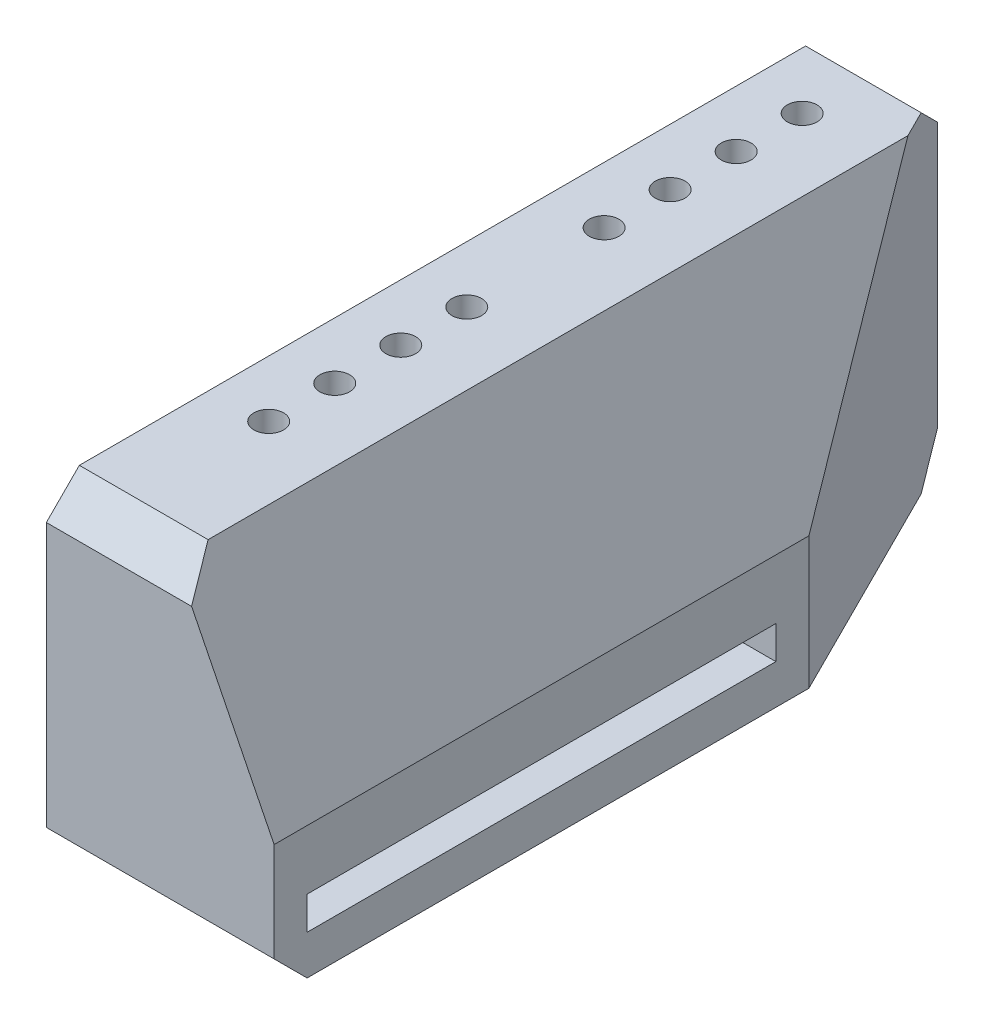
SolidWorks part; units mm, degrees
ref_plane "Front Plane" through (0, 0, 0) normal (0, 0, 1) x (1, 0, 0)
ref_plane "Top Plane" through (0, 0, 0) normal (0, 1, 0) x (1, 0, 0)
ref_plane "Right Plane" through (0, 0, 0) normal (1, 0, 0) x (0, 0, -1)
sketch "Sketch1" plane through (0, 0, 0) normal (1, 0, 0) x (0, 0, -1)
  line L1 (-60, -25) -> (60, -25)
  line L2 (-60, -25) -> (-60, 25)
  line L3 (-60, 25) -> (60, 25)
  line L4 (60, -25) -> (60, 25)
  line L5 (-60, -25) -> (60, 25) construction
  line L6 (-60, 25) -> (60, -25) construction
  point P0 (0, 0)
  dimension "D1" = 50
  dimension "D2" = 120
extrude "Boss-Extrude1" add sketch "Sketch1" along normal blind 34.5
sketch "Sketch2" plane through (34.5, 0, 0) normal (1, 0, 0) x (0, 0, -1)
  line L0 (-60, 25) -> (-60, -25) construction
  line L1 (-55, -19) -> (16, -19)
  line L2 (-55, -19) -> (-55, -14)
  line L3 (-55, -14) -> (16, -14)
  line L4 (16, -19) -> (16, -14)
  line L5 (-55, -19) -> (16, -14) construction
  line L6 (-55, -14) -> (16, -19) construction
  line L7 (-60, -25) -> (60, -25) construction
  point P0 (-19.5, -16.5)
  dimension "D1" = 71
  dimension "D2" = 5
  dimension "D3" = 5
  dimension "D4" = 6
extrude "Cut-Extrude1" cut sketch "Sketch2" against normal blind 16
hole_wizard "M4 Clearance Hole1" positions "Sketch3" profile "Sketch5" hole size "M4" standard "ANSI Metric"
sketch "Sketch3" plane through (0, -25, 0) normal (0, -1, 0) x (-1, 0, 0)
  line L0 (-24.5, -50) -> (-24.5, 10)
  line L2 (-34.5, -60) -> (-34.5, 60) construction
  line L3 (-34.5, -60) -> (0, -60) construction
  point P1 (-24.5, -50)
  point P2 (-24.5, 10)
  dimension "D1" = 10
  dimension "D2" = 10
  dimension "D3" = 60
sketch "Sketch5" plane through (24.5, -25, 50) normal (1, 0, 0) x (0, 0, -1)
  line L0 (0, 0) -> (0, 6)
  line L1 (0, 6) -> (2.25, 6)
  line L2 (2.25, 6) -> (2.25, 0)
  line L5 (2.25, 0) -> (0, 0)
  line L11 (0, -6.35) -> (0, 107.95) construction
  dimension "Thru Hole Dia." = 4.5
  dimension "Thru Hole Depth" = 6
hole_wizard "M4 Clearance Hole2" positions "Sketch6" profile "Sketch8" hole size "M4" standard "ANSI Metric"
sketch "Sketch6" plane through (0, 25, 0) normal (0, 1, 0) x (1, 0, 0)
  line L0 (8.58, 15.9) -> (8.58, -34.9)
  line L1 (0, 60) -> (0, -60) construction
  line L3 (34.5, -55) -> (34.5, 16) construction
  line L4 (34.5, -55) -> (34.5, 16)
  point P1 (8.58, 15.9)
  point P2 (8.58, -34.9)
  point P20 (8.58, -9.5)
  point P21 (34.5, -19.5)
  point P22 (8.58, 10.6774)
  dimension "D1" = 50.8
  dimension "D2" = 8.58
  dimension "D3" = 10
sketch "Sketch8" plane through (8.58, 25, -15.9) normal (1, 0, 0) x (0, 0, 1)
  line L0 (0, 0) -> (0, 7.3519)
  line L1 (0, 7.3519) -> (2.25, 6)
  line L2 (2.25, 6) -> (2.25, 0)
  line L5 (2.25, 0) -> (0, 0)
  line L10 (0, 7.3519) -> (-2.25, 6) construction
  line L11 (0, -6.35) -> (0, 107.95) construction
  dimension "Hole Dia." = 4.5
  dimension "Hole Depth" = 6
  dimension "Drill Angle" = 118
pattern_linear "LPattern1" count 4 spacing 10 along (0, 0, -1) of "M4 Clearance Hole2"
sketch "Sketch9" plane through (0, 0, 0) normal (-1, 0, 0) x (0, 0, 1)
  line L0 (-60, 25) -> (60, 25) construction
  line L1 (-51.4, 14) -> (-10.4, 14)
  line L2 (-51.4, 14) -> (-51.4, 19)
  line L3 (-51.4, 19) -> (-10.4, 19)
  line L4 (-10.4, 14) -> (-10.4, 19)
  line L5 (-51.4, 14) -> (-10.4, 19) construction
  line L6 (-51.4, 19) -> (-10.4, 14) construction
  line L7 (-0.6, 14) -> (40.4, 14)
  line L8 (-0.6, 14) -> (-0.6, 19)
  line L9 (-0.6, 19) -> (40.4, 19)
  line L10 (40.4, 14) -> (40.4, 19)
  line L11 (-0.6, 14) -> (40.4, 19) construction
  line L12 (-0.6, 19) -> (40.4, 14) construction
  line L13 (37.15, 25) -> (32.65, 25) construction
  line L14 (27.15, 25) -> (22.65, 25) construction
  line L15 (17.15, 25) -> (12.65, 25) construction
  line L16 (7.15, 25) -> (2.65, 25) construction
  line L17 (-13.65, 25) -> (-18.15, 25) construction
  line L18 (-23.65, 25) -> (-28.15, 25) construction
  line L19 (-33.65, 25) -> (-38.15, 25) construction
  line L20 (-43.65, 25) -> (-48.15, 25) construction
  line L21 (37.15, 25) -> (32.65, 25)
  line L22 (27.15, 25) -> (22.65, 25)
  line L23 (17.15, 25) -> (12.65, 25)
  line L24 (7.15, 25) -> (2.65, 25)
  line L25 (-13.65, 25) -> (-18.15, 25)
  line L26 (-23.65, 25) -> (-28.15, 25)
  line L27 (-33.65, 25) -> (-38.15, 25)
  line L28 (-43.65, 25) -> (-48.15, 25)
  point P0 (-30.9, 16.5)
  point P5 (19.9, 16.5)
  point P10 (0, 0)
  point P29 (-45.9, 25)
  point P30 (34.9, 25)
  point P31 (4.9, 25)
  point P32 (-15.9, 25)
  dimension "D1" = 5
  dimension "D2" = 6
  dimension "D3" = 5.5
  dimension "D4" = 5.5
  dimension "D5" = 5.5
  dimension "D6" = 5.5
extrude "Cut-Extrude2" cut sketch "Sketch9" against normal blind 16 contours L1 L4 L3 L2 | L7 L10 L9 L8
sketch "Sketch10" plane through (0, 25, 0) normal (0, 1, 0) x (1, 0, 0)
  line L1 (0, 60) -> (0, -60) construction
  line L3 (15, 60) -> (34.5, 21)
  line L4 (34.5, 60) -> (0, 60) construction
  line L5 (34.5, 60) -> (34.5, -60) construction
  line L10 (34.5, -55) -> (34.5, 16)
  line L11 (34.5, 16) -> (18.5, 16)
  line L12 (18.5, 16) -> (18.5, -55)
  line L13 (18.5, -55) -> (34.5, -55)
  line L14 (34.5, -55) -> (34.5, 16)
  line L15 (34.5, 16) -> (18.5, 16)
  line L16 (18.5, 16) -> (18.5, -55)
  line L17 (18.5, -55) -> (34.5, -55)
  line M11 (34.5, -60) -> (34.5, 60)
  line M12 (34.5, 60) -> (0, 60)
  dimension "D4" = 5
  dimension "D5" = 15
  dimension "D3" = 0
extrude "Cut-Extrude3" cut sketch "Sketch10" against normal through all contours L3 M12 M11
chamfer "Chamfer2" distance 15 distance2 30 1 edges at (34.5, 25, 19.5)
chamfer "Chamfer3" distance 5 angle 45 4 edges at (17.25, -25, 60) (7.5, -25, -60) (9.75, 25, 60) (7.5, 25, -60)
